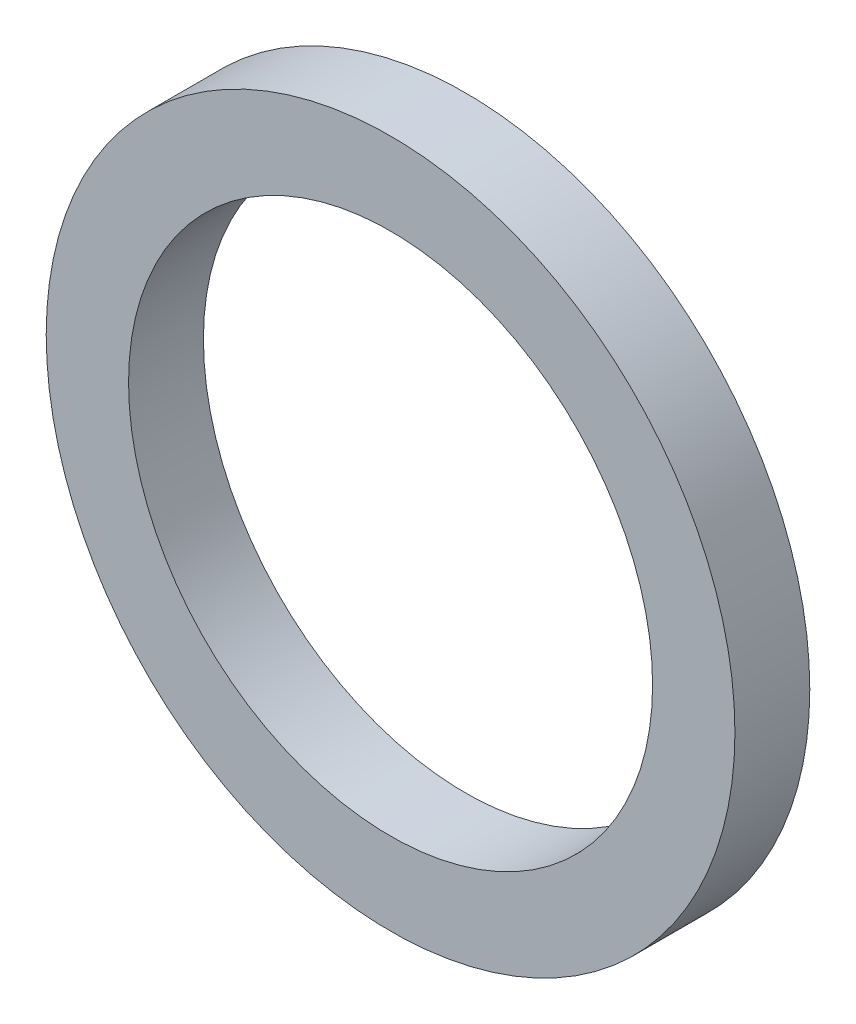
SolidWorks part; units mm, degrees
ref_plane "前视基准面" through (0, 0, 0) normal (0, 0, 1) x (1, 0, 0)
ref_plane "上视基准面" through (0, 0, 0) normal (0, 1, 0) x (1, 0, 0)
ref_plane "右视基准面" through (0, 0, 0) normal (1, 0, 0) x (0, 0, -1)
sketch "草图1" plane through (0, 0, 0) normal (0, 0, 1) x (1, 0, 0)
  circle A0 centre (0, 0) radius 46
  circle A1 centre (0, 0) radius 35
  dimension "d2" = 92
  dimension "d1" = 70
extrude "拉伸1" add sketch "草图1" along normal blind 10
